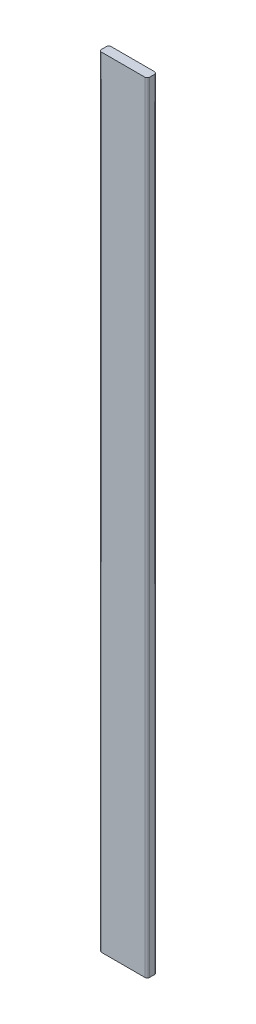
SolidWorks part; units mm, degrees
material "Сосна"
ref_plane "Спереди" through (0, 0, 0) normal (0, 0, 1) x (1, 0, 0)
ref_plane "Сверху" through (0, 0, 0) normal (0, 1, 0) x (1, 0, 0)
ref_plane "Справа" through (0, 0, 0) normal (1, 0, 0) x (0, 0, -1)
sketch "Эскиз1" plane through (0, 0, 0) normal (0, 0, 1) x (1, 0, 0)
  line L1 (-381.5789, 1547.6316) -> (-281.5789, 1547.6316)
  line L2 (-381.5789, 1547.6316) -> (-381.5789, -72.3684)
  line L3 (-381.5789, -72.3684) -> (-281.5789, -72.3684)
  line L4 (-281.5789, 1547.6316) -> (-281.5789, -72.3684)
  dimension "D1" = 100
  dimension "D2" = 1620
extrude "Бобышка-Вытянуть1" add sketch "Эскиз1" along normal blind 20
fillet "Скругление1" radius 5 4 edges at (-381.5789, 737.6316, 0) (-381.5789, 737.6316, 20) (-281.5789, 737.6316, 0) (-281.5789, 737.6316, 20)
